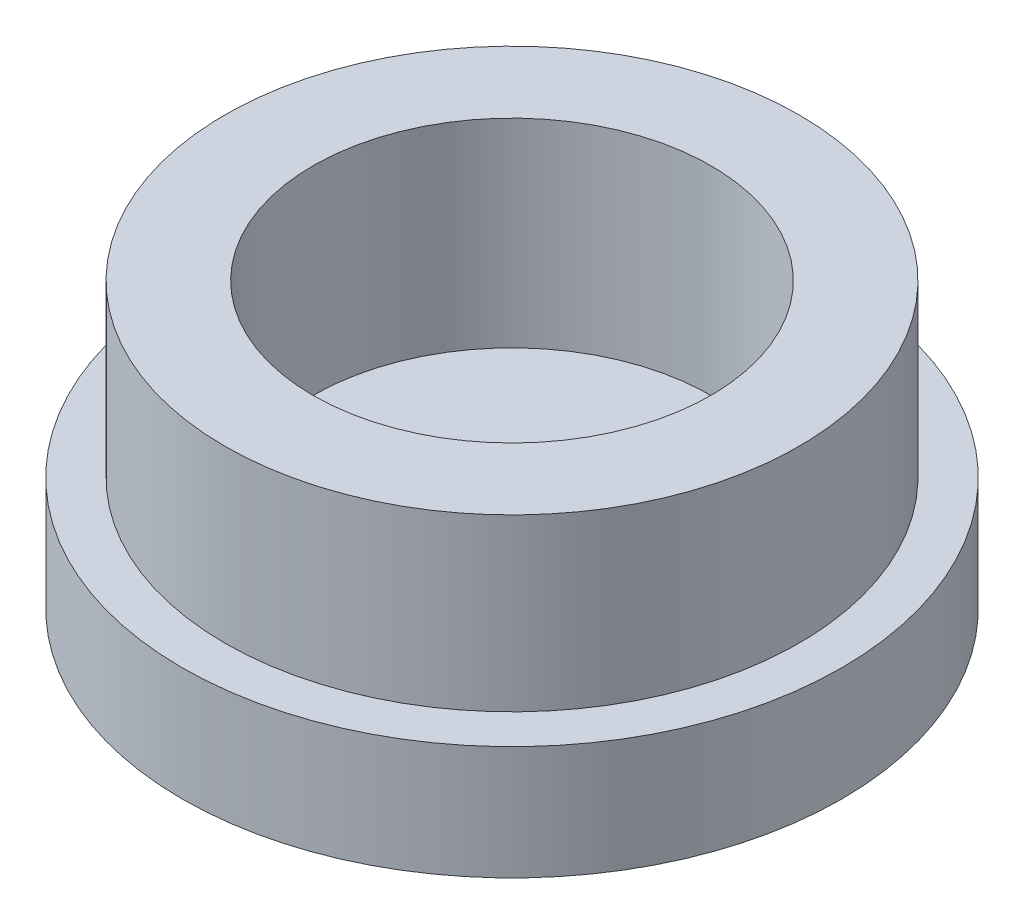
SolidWorks part; units mm, degrees
material "Polyetheretherketone (PEEK)"
ref_plane "Front Plane" through (0, 0, 0) normal (0, 0, 1) x (1, 0, 0)
ref_plane "Top Plane" through (0, 0, 0) normal (0, 1, 0) x (1, 0, 0)
ref_plane "Right Plane" through (0, 0, 0) normal (1, 0, 0) x (0, 0, -1)
sketch "Sketch1" plane through (0, 0, 0) normal (0, 1, 0) x (1, 0, 0)
  circle A0 centre (0, 0) radius 5.8
extrude "Boss-Extrude1" add sketch "Sketch1" along normal blind 5
sketch "Sketch2" plane through (0, 5, 0) normal (0, 1, 0) x (1, 0, 0)
  circle A0 centre (0, 0) radius 3.5
extrude "Cut-Extrude1" cut sketch "Sketch2" against normal blind 3.5
ref_plane "Plane1" through (0, 5, 0) normal (0, 1, 0) x (1, 0, 0)
sketch "Sketch3" plane through (0, 5, 0) normal (0, 1, 0) x (1, 0, 0)
  circle A0 centre (0, 0) radius 5.05
  circle A1 centre (0, 0) radius 8.2756
extrude "Cut-Extrude2" cut sketch "Sketch3" against normal blind 3
